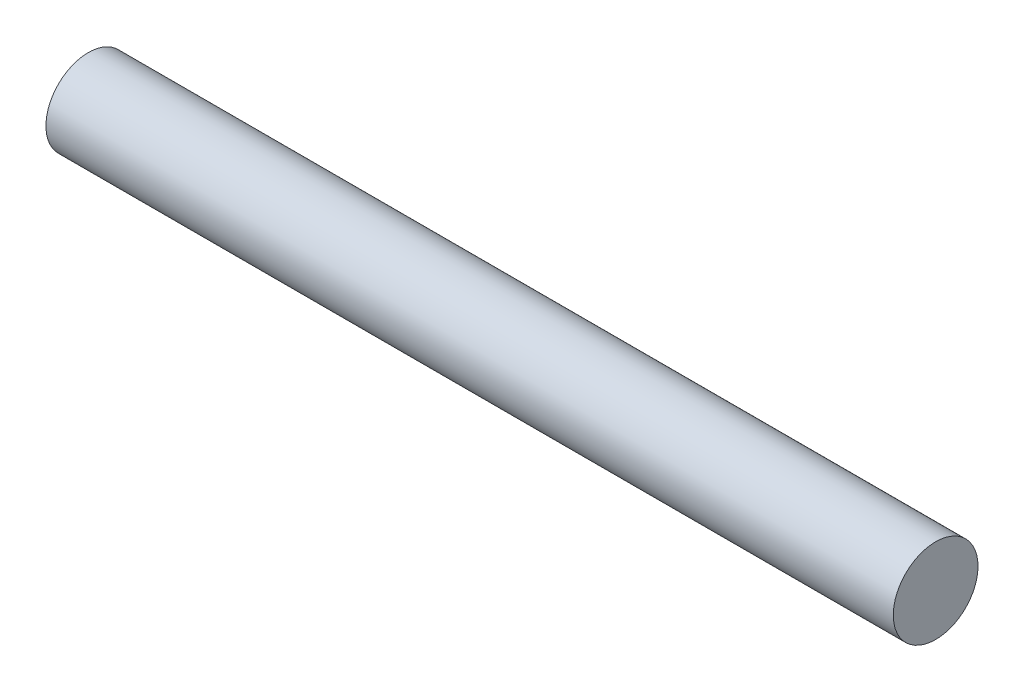
SolidWorks part; units mm, degrees
material "6061 Alloy"
ref_plane "Front Plane" through (0, 0, 0) normal (0, 0, 1) x (1, 0, 0)
ref_plane "Top Plane" through (0, 0, 0) normal (0, 1, 0) x (1, 0, 0)
ref_plane "Right Plane" through (0, 0, 0) normal (1, 0, 0) x (0, 0, -1)
sketch "Sketch2" plane through (0, 0, 0) normal (1, 0, 0) x (0, 0, -1)
  circle A0 centre (0, 0) radius 5
  dimension "D1" = 10
extrude "Boss-Extrude1" add sketch "Sketch2" along normal blind 100
